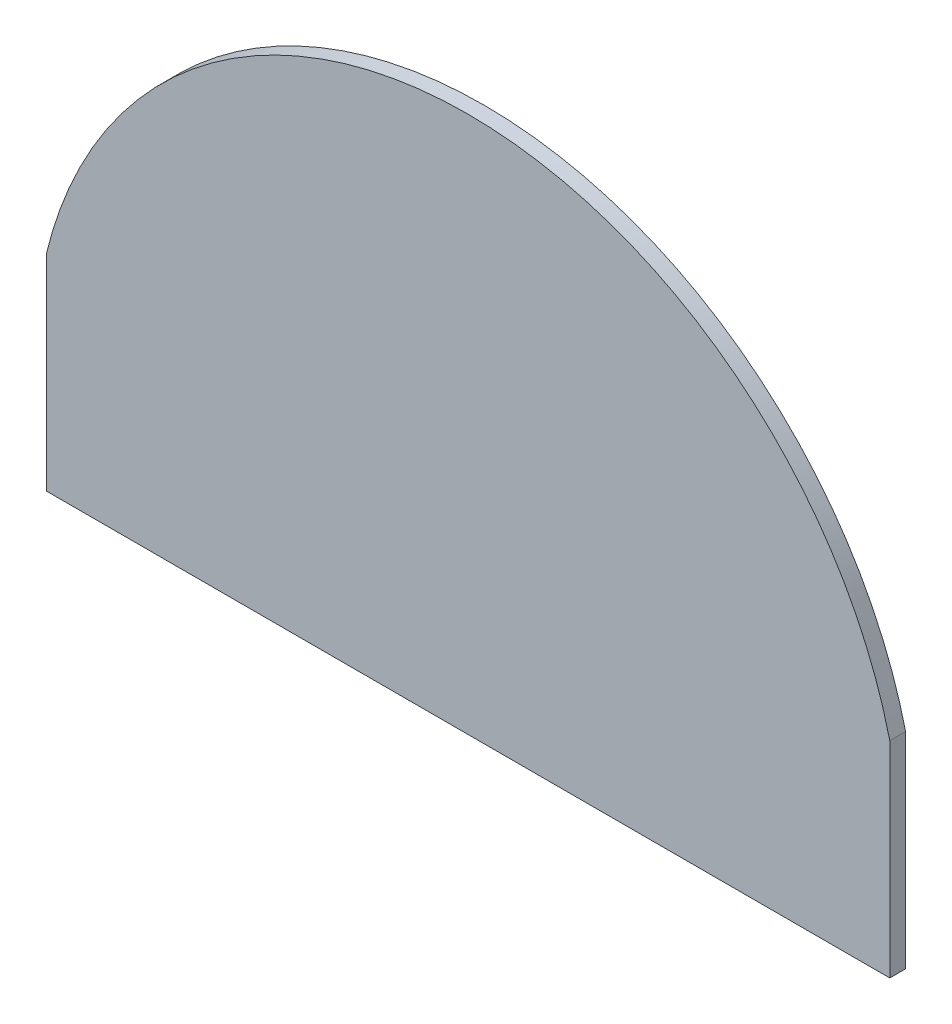
SolidWorks part; units mm, degrees
ref_plane "Front Plane" through (0, 0, 0) normal (0, 0, 1) x (1, 0, 0)
ref_plane "Top Plane" through (0, 0, 0) normal (0, 1, 0) x (1, 0, 0)
ref_plane "Right Plane" through (0, 0, 0) normal (1, 0, 0) x (0, 0, -1)
ref_plane "Plane35" through (0, 0, 50) normal (0, 0, 1) x (1, 0, 0)
sketch "Sketch1" plane through (0, 0, 50) normal (0, 0, 1) x (1, 0, 0)
  line L1 (-80, 44) -> (-80, 5)
  line L2 (80, 5) -> (-80, 5)
  line L6 (80, 44) -> (80, 5)
  spline S1 degree 2 poles (80, 44) (79.1856, 47.3595) (78.091, 50.643) (76.9964, 53.9262) (75.6327, 57.1005) (74.2696, 60.2734) (72.6431, 63.3249) (71.0182, 66.3735) (69.1465, 69.2714) (67.2771, 72.1656) (65.1695, 74.8967) (63.0654, 77.6234) (60.7441, 80.1616) (58.4274, 82.6949) (55.9044, 85.0291) (53.3875, 87.3577) (50.6886, 89.467) (45.4565, 93.5562) (39.6364, 96.7535) (33.5998, 100.0697) (27.0993, 102.336) (20.5644, 104.6143) (13.7401, 105.7698) (10.3332, 106.3466) (6.889, 106.6358) (3.448, 106.9246) (0, 106.9246) (-3.4491, 106.9246) (-6.889, 106.6358) (-10.3343, 106.3465) (-13.7401, 105.7698) (-20.5655, 104.614) (-27.0993, 102.336) (-33.6008, 100.0693) (-39.6364, 96.7535) (-45.4574, 93.5556) (-50.6886, 89.467) (-53.3883, 87.357) (-55.9044, 85.0291) (-58.4282, 82.6942) (-60.7441, 80.1616) (-63.0661, 77.6226) (-65.1695, 74.8967) (-67.2777, 72.1647) (-69.1465, 69.2714) (-71.0188, 66.3726) (-72.6431, 63.3249) (-74.2701, 60.2724) (-75.6327, 57.1005) (-76.9968, 53.9252) (-78.091, 50.643) (-79.1858, 47.359) (-80, 44) knots 0 0 0 0.03125 0.03125 0.0625 0.0625 0.09375 0.09375 0.125 0.125 0.15625 0.15625 0.1875 0.1875 0.21875 0.21875 0.25 0.25 0.3125 0.3125 0.375 0.375 0.4375 0.4375 0.46875 0.46875 0.5 0.5 0.53125 0.53125 0.5625 0.5625 0.625 0.625 0.6875 0.6875 0.75 0.75 0.78125 0.78125 0.8125 0.8125 0.84375 0.84375 0.875 0.875 0.90625 0.90625 0.9375 0.9375 0.96875 0.96875 1 1 1
extrude "Boss-Extrude2" add sketch "Sketch1" along normal blind 3
